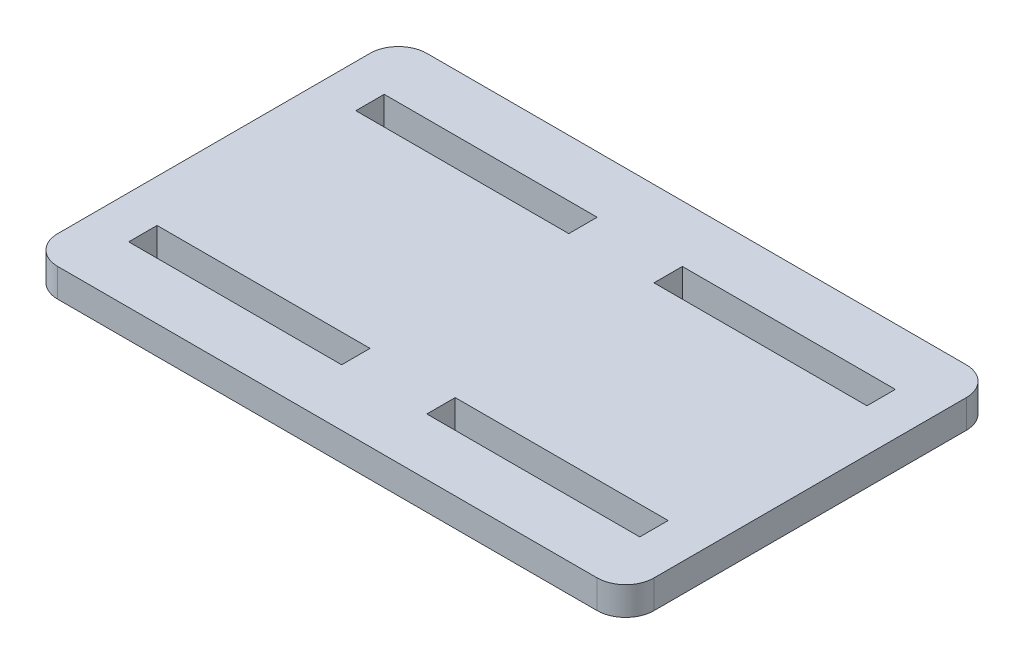
SolidWorks part; units mm, degrees
ref_plane "Front Plane" through (0, 0, 0) normal (0, 0, 1) x (1, 0, 0)
ref_plane "Top Plane" through (0, 0, 0) normal (0, 1, 0) x (1, 0, 0)
ref_plane "Right Plane" through (0, 0, 0) normal (1, 0, 0) x (0, 0, -1)
sketch "Sketch1" plane through (0, 0, 0) normal (1, 0, 0) x (0, 0, -1)
  line L0 (8.89, 0) -> (8.89, 2.54)
  line L1 (-8.89, 0) -> (-8.89, 2.54)
  line L2 (-8.89, 2.54) -> (8.89, 2.54)
  line L3 (-8.89, 0) -> (8.89, 0)
  point P0 (0, 0)
  dimension "D1" = 17.78
  dimension "D2" = 2.54
  dimension "D3" = 2.54
extrude "Boss-Extrude1" add sketch "Sketch1" along normal blind 11.43 contours L1 L3 L0 L2
sketch "Sketch2" plane through (0, 0, 0) normal (-1, 0, 0) x (0, 0, 1)
  line L0 (8.89, 0) -> (8.89, 2.54) construction
  line L1 (-8.89, 2.54) -> (8.89, 2.54)
  line L2 (-8.89, 2.54) -> (-8.89, 0)
  line L3 (-8.89, 0) -> (8.89, 0)
  line L4 (8.89, 2.54) -> (8.89, 0)
  dimension "D1" = 2.54
extrude "Boss-Extrude2" add sketch "Sketch2" along normal blind 15.24
mirror "Mirror1" about plane through (-15.24, 0, 0) normal (-1, 0, 0) of bodies 102 103
ref_plane "Plane1" through (11.43, 2.54, 8.89) normal (-1, 0, 0) x (0, 0, 1)
sketch "Sketch6" plane through (0, 0, -8.89) normal (0, 0, -1) x (-1, 0, 0)
  line L0 (41.91, 0) -> (41.91, 2.54) construction
  line L1 (-11.43, 2.54) -> (41.91, 2.54)
  line L2 (-11.43, 2.54) -> (-11.43, 0)
  line L3 (-11.43, 0) -> (41.91, 0)
  line L4 (41.91, 2.54) -> (41.91, 0)
  dimension "D1" = 2.54
sketch "Sketch7" plane through (0, 0, 8.89) normal (0, 0, 1) x (1, 0, 0)
  line L0 (11.43, 17.2085) -> (11.43, -12.1285) construction
  line L1 (-41.91, 2.54) -> (11.43, 2.54)
  line L2 (-41.91, 2.54) -> (-41.91, 0)
  line L3 (-41.91, 0) -> (11.43, 0)
  line L4 (11.43, 2.54) -> (11.43, 0)
  dimension "D1" = 2.54
ref_plane "Plane2" through (-15.24, 0, 0) normal (-1, 0, 0) x (0, 0, 1)
sketch "Sketch16" plane through (0, 0, 8.89) normal (0, 0, 1) x (1, 0, 0)
  line L0 (11.43, 0) -> (-41.91, 0) construction
  line L1 (-41.91, 2.54) -> (-38.1, 2.54)
  line L2 (-41.91, 2.54) -> (-41.91, 0)
  line L3 (-41.91, 0) -> (-38.1, 0)
  line L4 (-38.1, 2.54) -> (-38.1, 0)
  line L5 (11.43, 2.54) -> (-41.91, 2.54) construction
  line L6 (-15.24, 0) -> (-19.05, 0)
  line L7 (-15.24, 0) -> (-15.24, 2.54)
  line L8 (-15.24, 2.54) -> (-19.05, 2.54)
  line L9 (-19.05, 0) -> (-19.05, 2.54)
  point P13 (0, 0)
  line M3 (11.43, 2.54) -> (-41.91, 2.54)
  line M5 (-41.91, 0) -> (11.43, 0)
  dimension "D1" = 3.81
  dimension "D2" = 3.81
extrude "Boss-Extrude10" add sketch "Sketch16" along normal blind 7.62 contours L9 L7 M5 M3 | L4 L3 L2 L1
sketch "Sketch17" plane through (-19.05, 0, 0) normal (-1, 0, 0) x (0, 0, 1)
  line L0 (16.51, 2.54) -> (8.89, 2.54) construction
  line L1 (16.51, 0) -> (11.43, 0)
  line L2 (16.51, 0) -> (16.51, 2.54)
  line L3 (16.51, 2.54) -> (11.43, 2.54)
  line L4 (11.43, 0) -> (11.43, 2.54)
  dimension "D1" = 5.08
extrude "Boss-Extrude11" add sketch "Sketch17" along normal up to next
mirror "Mirror2" about plane through (-15.24, 0, 0) normal (-1, 0, 0) of "Boss-Extrude11", "Boss-Extrude10"
mirror "Mirror3" about plane through (0, 0, 0) normal (0, 0, 1) of "Mirror2", "Boss-Extrude11", "Boss-Extrude10"
sketch "Sketch18" plane through (0, 0, 0) normal (0, -1, 0) x (1, 0, 0)
  line L1 (-5.08, 8.89) -> (0, 8.89)
  line L2 (-5.08, 8.89) -> (-5.08, -8.89)
  line L3 (-5.08, -8.89) -> (0, -8.89)
  line L4 (0, 8.89) -> (0, -8.89)
  line L5 (11.43, -8.89) -> (-41.91, -8.89) construction
  line L6 (11.43, 16.51) -> (11.43, -16.51) construction
  dimension "D1" = 5.08
  dimension "D2" = 17.78
  dimension "D3" = 11.43
extrude "Boss-Extrude12" add sketch "Sketch18" along normal blind 5.08
sketch "Sketch19" plane through (-5.08, 0, 0) normal (-1, 0, 0) x (0, 0, 1)
  line L0 (8.89, -5.08) -> (8.89, 0) construction
  line L1 (-8.89, -5.08) -> (8.89, -5.08)
  line L2 (-8.89, -5.08) -> (-8.89, -2.54)
  line L3 (-8.89, -2.54) -> (8.89, -2.54)
  line L4 (8.89, -5.08) -> (8.89, -2.54)
extrude "Boss-Extrude13" add sketch "Sketch19" along normal blind 5.08
mirror "Mirror4" about plane through (-15.24, 0, 0) normal (-1, 0, 0) of "Boss-Extrude12", "Boss-Extrude13"
fillet "Fillet1" radius 2.54 4 edges at (-41.91, 1.27, -16.51) (11.43, 1.27, -16.51) (-41.91, 1.27, 16.51) (11.43, 1.27, 16.51)
